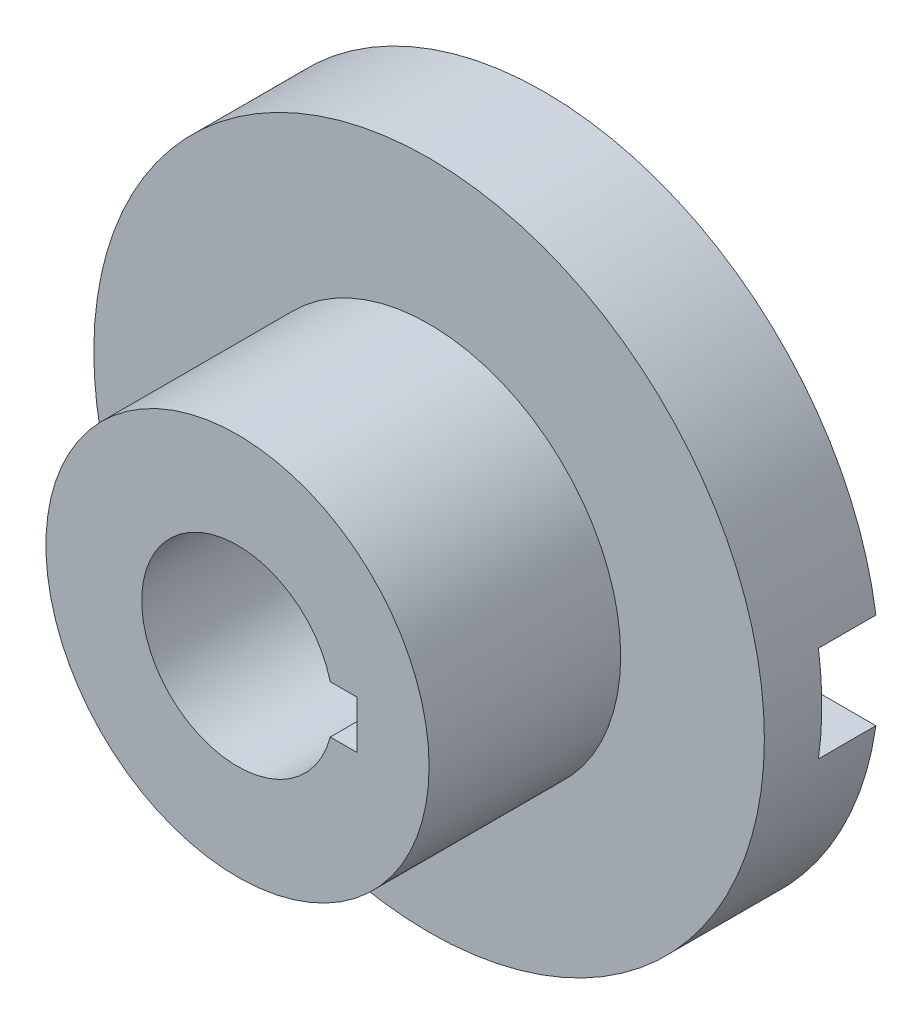
SolidWorks part; units mm, degrees
ref_plane "Front Plane" through (0, 0, 0) normal (0, 0, 1) x (1, 0, 0)
ref_plane "Top Plane" through (0, 0, 0) normal (0, 1, 0) x (1, 0, 0)
ref_plane "Right Plane" through (0, 0, 0) normal (1, 0, 0) x (0, 0, -1)
sketch "Sketch1" plane through (0, 0, 0) normal (0, 0, 1) x (1, 0, 0)
  circle A0 centre (0, 0) radius 35
  dimension "D1" = 70
extrude "Boss-Extrude1" add sketch "Sketch1" along normal mid plane 12
sketch "Sketch2" plane through (0, 0, 6) normal (0, 0, 1) x (1, 0, 0)
  circle A0 centre (0, 0) radius 20
  circle A1 centre (0, 0) radius 10
  dimension "D1" = 20
  dimension "D2" = 40
extrude "Boss-Extrude2" add sketch "Sketch2" along normal blind 20
sketch "Sketch3" plane through (0, 0, 6) normal (0, 0, 1) x (1, 0, 0)
  circle A0 centre (0, 0) radius 10 construction
  circle A1 centre (0, 0) radius 10
extrude "Cut-Extrude1" cut sketch "Sketch3" against normal blind 20
sketch "Sketch4" plane through (0, 0, 26) normal (0, 0, 1) x (1, 0, 0)
  line L1 (7.5, 2.5) -> (12.5, 2.5)
  line L2 (7.5, 2.5) -> (7.5, -2.5)
  line L3 (7.5, -2.5) -> (12.5, -2.5)
  line L4 (12.5, 2.5) -> (12.5, -2.5)
  line L5 (7.5, 2.5) -> (12.5, -2.5) construction
  line L6 (7.5, -2.5) -> (12.5, 2.5) construction
  circle A0 centre (0, 0) radius 10 construction
  point P0 (10, 0)
  point P7 (0, 0)
  point P8 (0, 0)
  point P9 (0, 0)
  point P10 (0, 0)
  point P11 (0, 0)
  point P12 (0, 0)
  point P13 (0, 0)
  point P15 (0, 0)
  dimension "D1" = 5
  dimension "D2" = 5
extrude "Cut-Extrude2" cut sketch "Sketch4" against normal through all
sketch "Sketch5" plane through (0, 0, -6) normal (0, 0, -1) x (-1, 0, 0)
  line L1 (41.0164, -5) -> (-41.0164, -5)
  line L2 (41.0164, -5) -> (41.0164, 5)
  line L3 (41.0164, 5) -> (-41.0164, 5)
  line L4 (-41.0164, -5) -> (-41.0164, 5)
  line L5 (41.0164, -5) -> (-41.0164, 5) construction
  line L6 (41.0164, 5) -> (-41.0164, -5) construction
  point P0 (0, 0)
  dimension "D1" = 10
extrude "Cut-Extrude3" cut sketch "Sketch5" against normal blind 6
